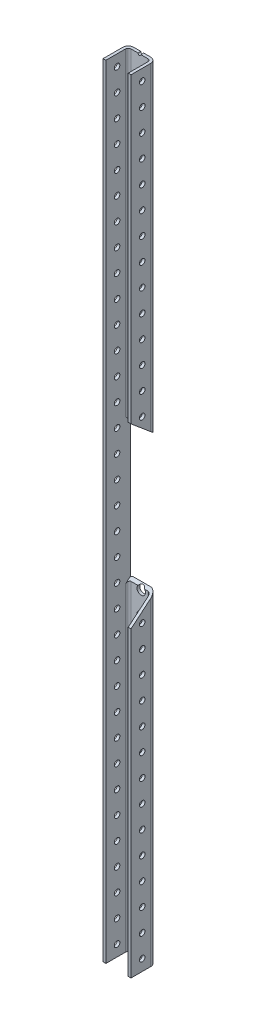
SolidWorks part; units mm, degrees
ref_plane "Front Plane" through (0, 0, 0) normal (0, 0, 1) x (1, 0, 0)
ref_plane "Top Plane" through (0, 0, 0) normal (0, 1, 0) x (1, 0, 0)
ref_plane "Right Plane" through (0, 0, 0) normal (1, 0, 0) x (0, 0, -1)
sketch "Sketch2" plane through (0, 0, 0) normal (0, 1, 0) x (1, 0, 0)
  line L0 (-12.7, 0) -> (12.7, 0) construction
  line L1 (-12.7, 0) -> (-12.7, 22.225)
  line L2 (-9.525, 25.4) -> (9.525, 25.4)
  line L3 (12.7, 22.225) -> (12.7, 0)
  line L4 (-15.875, 0) -> (-15.875, 22.225)
  line L5 (-9.525, 28.575) -> (9.525, 28.575)
  line L6 (15.875, 22.225) -> (15.875, 0)
  line L7 (-15.875, 0) -> (-12.7, 0)
  line L8 (12.7, 0) -> (15.875, 0)
  line L9 (-12.7, 25.4) -> (12.7, 25.4) construction
  line L10 (12.7, 25.4) -> (12.7, 0) construction
  line L11 (-12.7, 0) -> (-12.7, 25.4) construction
  line L12 (-15.875, 28.575) -> (15.875, 28.575) construction
  line L13 (15.875, 28.575) -> (15.875, 0) construction
  line L14 (-15.875, 0) -> (-15.875, 28.575) construction
  arc A0 (9.525, 25.4) -> (12.7, 22.225) centre (9.525, 22.225) cw
  arc A1 (-12.7, 22.225) -> (-9.525, 25.4) centre (-9.525, 22.225) cw
  arc A2 (9.525, 28.575) -> (15.875, 22.225) centre (9.525, 22.225) cw
  arc A3 (-15.875, 22.225) -> (-9.525, 28.575) centre (-9.525, 22.225) cw
  dimension "D4" = 3.175
  dimension "D5" = 6.35
  dimension "D1" = 25.4
  dimension "D2" = 25.4
  dimension "D3" = 3.175
extrude "Boss-Extrude1" add sketch "Sketch2" along normal mid plane 889
sketch "Sketch3" plane through (0, 0, -28.575) normal (0, 0, -1) x (-1, 0, 0)
  line L0 (0, 444.5) -> (0, -444.5) construction
  line L1 (-9.525, 444.5) -> (9.525, 444.5) construction
  line L2 (-9.525, -444.5) -> (9.525, -444.5) construction
  line L3 (-2.032, 444.5) -> (-2.032, -444.5) construction
  circle A0 centre (0, 444.5) radius 1.651
  circle A1 centre (-2.032, 361.95) radius 4.826
  circle A2 centre (-2.032, 336.55) radius 4.826
  circle A3 centre (-2.032, 107.95) radius 4.826
  circle A4 centre (-2.032, 82.55) radius 4.826
  circle A5 centre (-2.032, -107.95) radius 4.826
  circle A6 centre (-2.032, -82.55) radius 4.826
  circle A7 centre (0, -241.3) radius 1.5875
  circle A8 centre (0, 118.11) radius 3.175
  circle A9 centre (-2.032, -336.55) radius 4.826
  circle A10 centre (-2.032, -361.95) radius 4.826
  circle A11 centre (0, 159.512) radius 3.175
  circle A12 centre (0, -159.512) radius 3.175
  circle A13 centre (0, -118.11) radius 3.175
  dimension "D1" = 3.302
  dimension "D3" = 9.652
  dimension "D12" = 3.175
  dimension "D14" = 6.35
  dimension "D2" = 2.032
  dimension "D4" = 82.55
  dimension "D5" = 25.4
  dimension "D6" = 254
  dimension "D7" = 25.4
  dimension "D8" = 25.4
  dimension "D9" = 25.4
  dimension "D10" = 82.55
  dimension "D11" = 95.25
  dimension "D13" = 228.6
  dimension "D15" = 10.16
  dimension "D16" = 41.402
  dimension "D17" = 10.16
  dimension "D18" = 41.402
extrude "Cut-Extrude1" cut sketch "Sketch3" against normal through all
sketch "Sketch4" plane through (15.875, 0, 0) normal (1, 0, 0) x (0, 0, -1)
  line L1 (0, 444.5) -> (22.225, 444.5) construction
  line L2 (0, 444.5) -> (0, -444.5) construction
  circle A0 centre (12.7, 431.8) radius 3.175
  dimension "D2" = 6.35
  dimension "D1" = 12.7
  dimension "D3" = 12.7
extrude "Cut-Extrude2" cut sketch "Sketch4" against normal through all
pattern_linear "LPattern1" count 35 spacing 25.4 along (0, -1, 0) of "Cut-Extrude2"
sketch "Sketch5" plane through (0, 0, 0) normal (1, 0, 0) x (0, 0, -1)
  line L0 (0, 100.838) -> (0, -100.838)
  line L1 (0, 444.5) -> (0, -444.5) construction
  line L2 (0, -100.838) -> (28.575, -76.835)
  line L3 (28.575, 444.5) -> (28.575, -444.5) construction
  line L4 (28.575, -76.835) -> (28.575, 76.835)
  line L5 (28.575, 76.835) -> (0, 100.838)
  point P8 (28.575, 0)
  dimension "D1" = 153.67
  dimension "D2" = 201.676
extrude "Cut-Extrude3" cut sketch "Sketch5" along normal through all from offset 12.7
